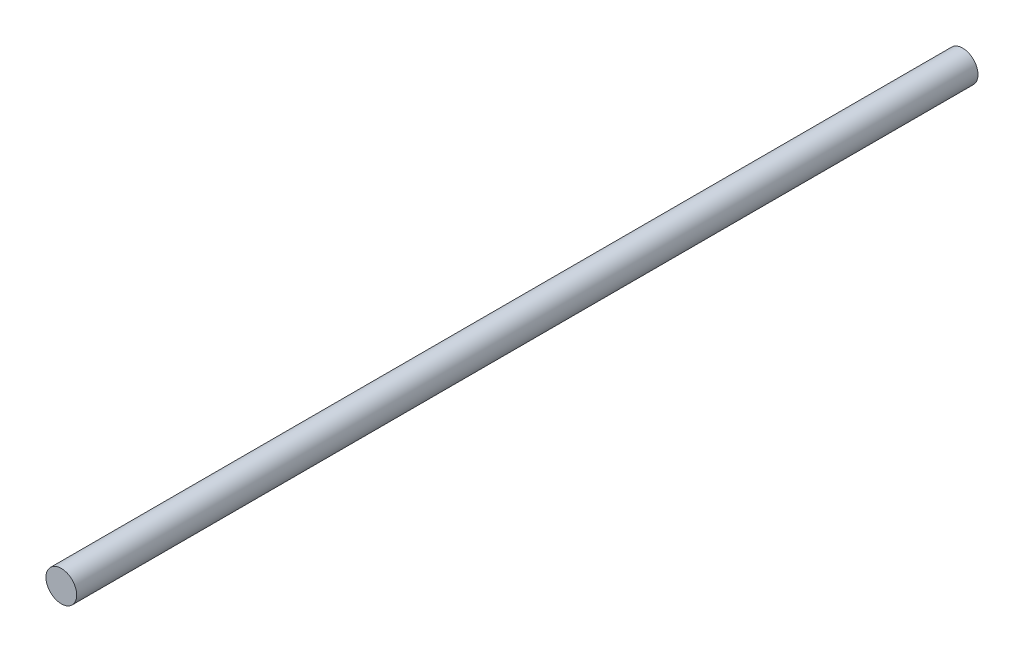
SolidWorks part; units mm, degrees
ref_plane "Front Plane" through (0, 0, 0) normal (0, 0, 1) x (1, 0, 0)
ref_plane "Top Plane" through (0, 0, 0) normal (0, 1, 0) x (1, 0, 0)
ref_plane "Right Plane" through (0, 0, 0) normal (1, 0, 0) x (0, 0, -1)
sketch "Sketch1" plane through (0, 0, 0) normal (0, 0, 1) x (1, 0, 0)
  circle A0 centre (0, 0) radius 1.5
  dimension "D1" = 3
extrude "Boss-Extrude1" add sketch "Sketch1" along normal blind 88
